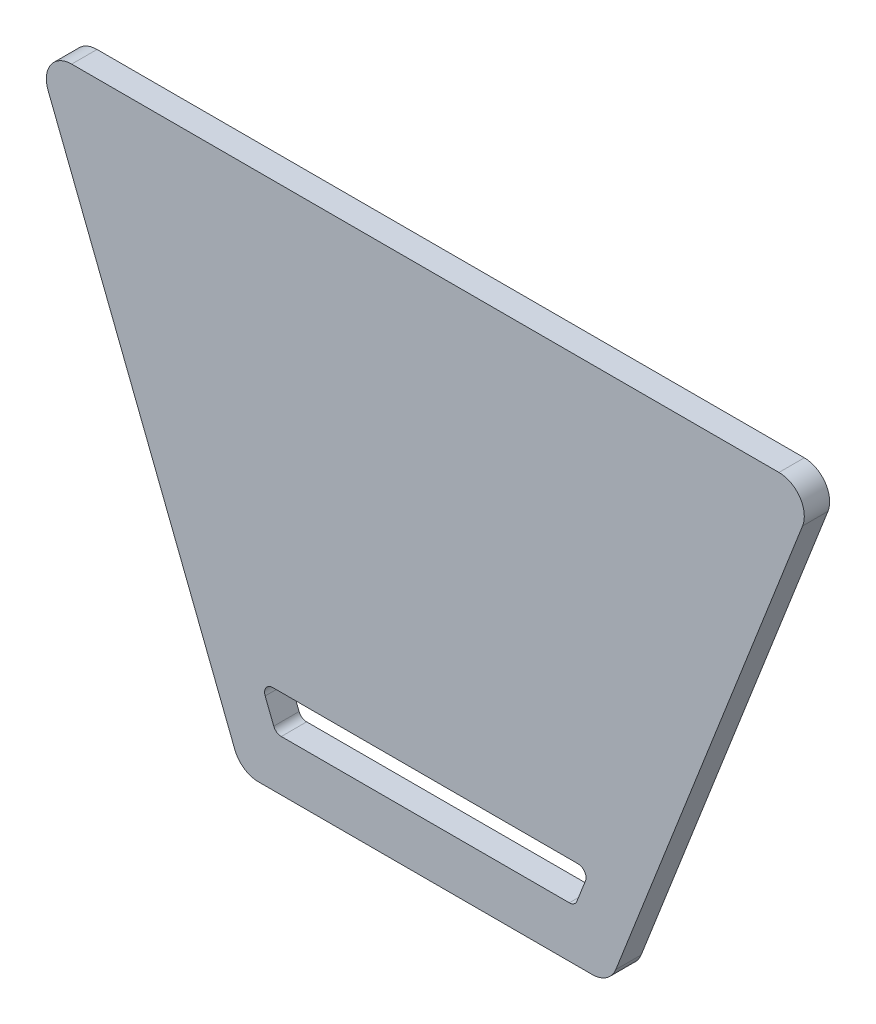
SolidWorks part; units mm, degrees
ref_plane "Front Plane" through (0, 0, 0) normal (0, 0, 1) x (1, 0, 0)
ref_plane "Top Plane" through (0, 0, 0) normal (0, 1, 0) x (1, 0, 0)
ref_plane "Right Plane" through (0, 0, 0) normal (1, 0, 0) x (0, 0, -1)
sketch "Sketch1" plane through (0, 0, 0) normal (0, 0, 1) x (1, 0, 0)
  line L0 (-18.2571, 0) -> (2.6408, 0)
  line L2 (28.9831, 61.8157) -> (5.5977, 2.0186)
  line L3 (-18.2571, 66.147) -> (26.0261, 66.147)
  line L4 (-18.2571, 66.147) -> (-18.2571, 0)
  arc A0 (2.6408, 0) -> (5.5977, 2.0186) centre (2.6408, 3.175) ccw
  arc A1 (26.0261, 66.147) -> (28.9831, 61.8157) centre (26.0261, 62.972) cw
  point P0 (0, 0)
  dimension "D1" = 3.175
extrude "Extrude1" add sketch "Sketch1" against normal blind 3.175
mirror "Mirror1" about plane through (-18.2571, 66.147, -3.175) normal (-1, 0, 0) of bodies 101
sketch "Sketch2" plane through (0, 0, 0) normal (0, 0, 1) x (1, 0, 0)
  line L0 (5.5977, 2.0186) -> (28.9831, 61.8157) construction
  line L1 (5.5977, 2.0186) -> (28.9831, 61.8157)
  line L2 (0.7259, 6.996) -> (1.7988, 9.7392)
  line L3 (-36.2939, 6.35) -> (-0.2203, 6.35)
  line L4 (0.8525, 11.1252) -> (-37.3667, 11.1252)
  line L6 (-0.3161, 4.3314) -> (23.0692, 64.1284) construction
  line L7 (-37.2401, 6.996) -> (-38.3129, 9.7392)
  line L8 (-39.155, 0) -> (2.6408, 0) construction
  line L9 (-18.2571, 6.35) -> (-18.2571, 11.1252) construction
  arc A0 (1.7988, 9.7392) -> (0.8525, 11.1252) centre (0.8525, 10.1092) ccw
  arc A1 (-0.2203, 6.35) -> (0.7259, 6.996) centre (-0.2203, 7.366) ccw
  arc A2 (-36.2939, 6.35) -> (-37.2401, 6.996) centre (-36.2939, 7.366) cw
  arc A3 (-38.3129, 9.7392) -> (-37.3667, 11.1252) centre (-37.3667, 10.1092) cw
  point P18 (-18.2571, 0)
  dimension "D3" = 1.016
  dimension "D4" = 6.35
  dimension "D5" = 4.7752
  dimension "D1" = 6.35
extrude "Extrude2" cut sketch "Sketch2" against normal through all contours L3 A1 L2 A0 L4 A3 L7 A2
